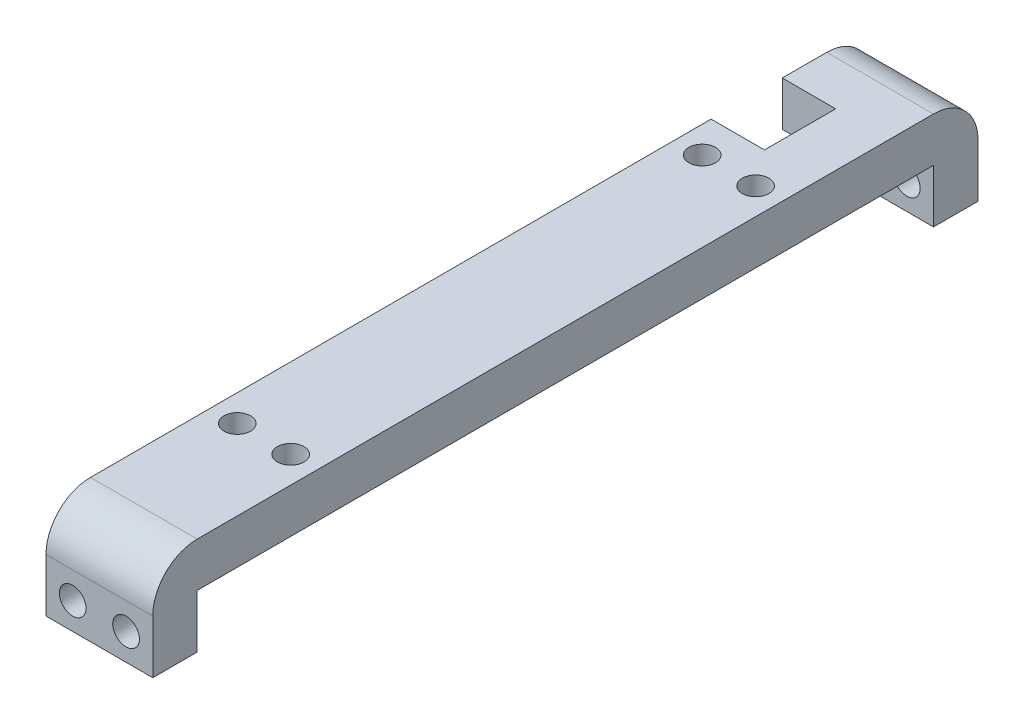
SolidWorks part; units mm, degrees
ref_plane "Front" through (0, 0, 0) normal (0, 0, 1) x (1, 0, 0)
ref_plane "Top" through (0, 0, 0) normal (0, 1, 0) x (1, 0, 0)
ref_plane "Right" through (0, 0, 0) normal (1, 0, 0) x (0, 0, -1)
sketch "Sketch1" plane through (0, 0, 0) normal (0, 0, 1) x (1, 0, 0)
  line L1 (-6, 5.5) -> (6, 5.5)
  line L2 (-6, 5.5) -> (-6, -5.5)
  line L3 (-6, -5.5) -> (6, -5.5)
  line L4 (6, 5.5) -> (6, -5.5)
  dimension "D1" = 6
  dimension "D2" = 6
  dimension "D3" = 5.5
  dimension "D4" = 5.5
extrude "Extrude1" add sketch "Sketch1" along normal blind 5
sketch "Sketch2" plane through (0, 0, 5) normal (0, 0, 1) x (1, 0, 0)
  line L0 (6, -5.5) -> (6, 5.5) construction
  line L1 (-6, 5.5) -> (6, 5.5)
  line L2 (-6, 5.5) -> (-6, 0.5)
  line L3 (-6, 0.5) -> (6, 0.5)
  line L4 (6, 5.5) -> (6, 0.5)
  dimension "D1" = 5
extrude "Extrude2" add sketch "Sketch2" along normal blind 82.76
sketch "Sketch3" plane through (0, 0, 87.76) normal (0, 0, 1) x (1, 0, 0)
  line L1 (-6, 5.5) -> (6, 5.5)
  line L2 (-6, 5.5) -> (-6, -5.5)
  line L3 (-6, -5.5) -> (6, -5.5)
  line L4 (6, 5.5) -> (6, -5.5)
extrude "Extrude3" add sketch "Sketch3" along normal blind 5
sketch "Sketch5" plane through (0, 0, 0) normal (0, 0, -1) x (-1, 0, 0)
  line L0 (6, -5.5) -> (-6, -5.5) construction
  line L1 (-6, -5.5) -> (-6, 5.5) construction
  line L2 (6, 5.5) -> (6, -5.5) construction
  circle A0 centre (-3, -2.5) radius 1.5
  circle A1 centre (3, -2.5) radius 1.5
  dimension "D1" = 3
  dimension "D2" = 3
  dimension "D4" = 3
  dimension "D5" = 3
  dimension "D3" = 3
  dimension "D6" = 3
extrude "Extrude4" cut sketch "Sketch5" against normal up to surface (92.76 mm away) up to face at (0, 0, 92.76)
sketch "Sketch8" plane through (0, 5.5, 0) normal (0, 1, 0) x (1, 0, 0)
  line L0 (-6, -92.76) -> (-6, 0) construction
  line L1 (-6, -10) -> (0, -10)
  line L2 (-6, -10) -> (-6, -18)
  line L3 (-6, -18) -> (0, -18)
  line L4 (0, -10) -> (0, -18)
  line L5 (6, 0) -> (-6, 0) construction
  dimension "D1" = 10
  dimension "D2" = 8
  dimension "D3" = 6
extrude "Extrude5" cut sketch "Sketch8" against normal up to surface (5 mm away) up to face at (-3, 0.5, 67.07)
sketch "Sketch9" plane through (0, 5.5, 0) normal (0, 1, 0) x (1, 0, 0)
  line L0 (6, 0) -> (-6, 0) construction
  line L1 (6, -92.76) -> (6, 0) construction
  line L2 (-6, -92.76) -> (-6, -18) construction
  line L3 (6, -92.76) -> (-6, -92.76) construction
  circle A0 centre (-3, -22) radius 1.5
  circle A1 centre (3, -22) radius 1.5
  circle A2 centre (3, -74.26) radius 1.5
  circle A3 centre (-3, -74.26) radius 1.5
  dimension "D1" = 3
  dimension "D2" = 3
  dimension "D5" = 3
  dimension "D6" = 3
  dimension "D7" = 3
  dimension "D8" = 3
  dimension "D10" = 3
  dimension "D11" = 18.5
  dimension "D12" = 18.5
  dimension "D3" = 22
  dimension "D4" = 22
  dimension "D9" = 3
extrude "Extrude6" cut sketch "Sketch9" against normal up to surface (5 mm away) up to face at (-3, 0.5, 40.035)
fillet "Fillet1" radius 5 2 edges at (0, 5.5, 92.76) (0, 5.5, 0)
